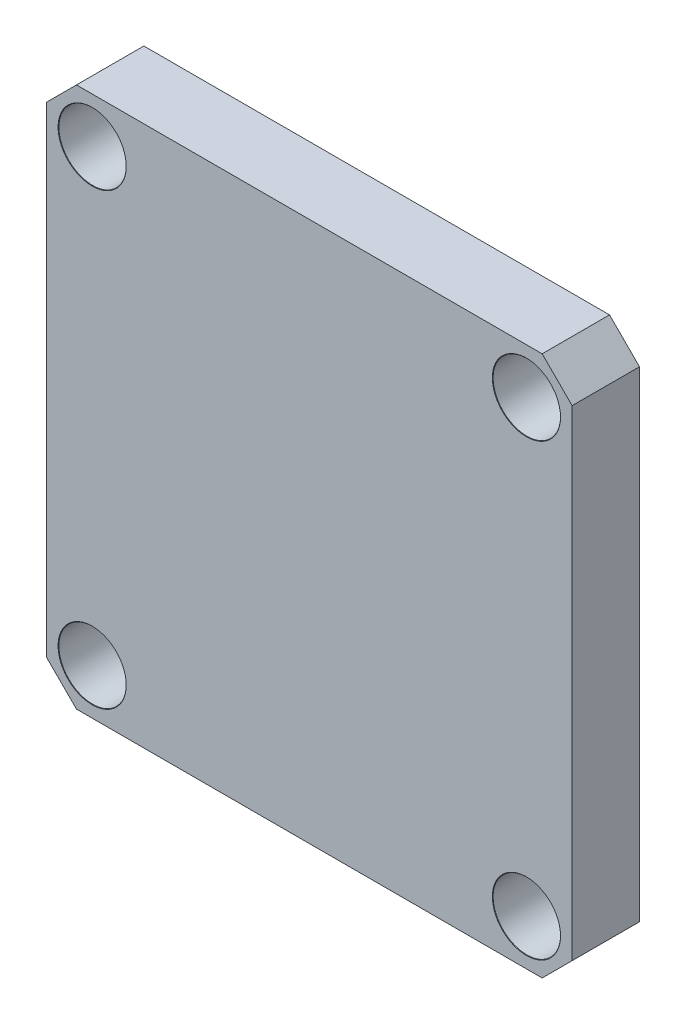
SolidWorks part; units mm, degrees
ref_plane "Спереди" through (0, 0, 0) normal (0, 0, 1) x (1, 0, 0)
ref_plane "Сверху" through (0, 0, 0) normal (0, 1, 0) x (1, 0, 0)
ref_plane "Справа" through (0, 0, 0) normal (1, 0, 0) x (0, 0, -1)
sketch "Эскиз1" plane through (0, 0, 0) normal (0, 0, 1) x (1, 0, 0)
  line L1 (-17.55, -18.05) -> (17.55, -18.05)
  line L2 (-17.55, -18.05) -> (-17.55, 18.05)
  line L3 (-17.55, 18.05) -> (17.55, 18.05)
  line L4 (17.55, -18.05) -> (17.55, 18.05)
  line L5 (-17.55, -18.05) -> (17.55, 18.05) construction
  line L6 (-17.55, 18.05) -> (17.55, -18.05) construction
  point P0 (0, 0)
  dimension "D1" = 35.1
  dimension "D2" = 36.1
extrude "Бобышка-Вытянуть1" add sketch "Эскиз1" along normal blind 4.5
chamfer "Фаска1" distance 2 angle 45 4 edges at (-17.55, -18.05, 2.25) (17.55, -18.05, 2.25) (17.55, 18.05, 2.25) (-17.55, 18.05, 2.25)
sketch "Эскиз2" plane through (0, 0, 4.5) normal (0, 0, 1) x (1, 0, 0)
  line L1 (-14.5, -15) -> (14.5, -15)
  line L2 (-14.5, -15) -> (-14.5, 15)
  line L3 (-14.5, 15) -> (14.5, 15)
  line L4 (14.5, -15) -> (14.5, 15)
  line L5 (-14.5, -15) -> (14.5, 15) construction
  line L6 (-14.5, 15) -> (14.5, -15) construction
  point P0 (0, 0)
  dimension "D1" = 29
  dimension "D2" = 30
hole_wizard "Отверстие с зазором M41" positions "Трехмерный эскиз1" profile "Эскиз3" hole size "M4" standard "ISO" end condition through all
sketch3d "Трехмерный эскиз1"
  point P0 (-14.5, 15, 4.5)
  point P3 (14.5, 15, 4.5)
  point P6 (14.5, -15, 4.5)
  point P9 (-14.5, -15, 4.5)
sketch "Эскиз3" plane through (-14.5, 15, 4.5) normal (1, 0, 0) x (0, -1, 0)
  line L0 (0, 0) -> (0, 4.5)
  line L1 (0, 4.5) -> (2.25, 4.5)
  line L2 (2.25, 4.5) -> (2.25, 0.025)
  line L3 (2.25, 0.025) -> (2.275, 0)
  line L5 (2.275, 0) -> (0, 0)
  line L6 (-2.25, 0.025) -> (-2.275, 0) construction
  line L11 (0, -6.35) -> (0, 107.95) construction
  dimension "Диаметр сквозного отверстия" = 4.5
  dimension "Глубина сквозного отверстия" = 4.5
  dimension "Диаметр передней зенковки" = 4.55
  dimension "Угол передней зенковки" = 90
